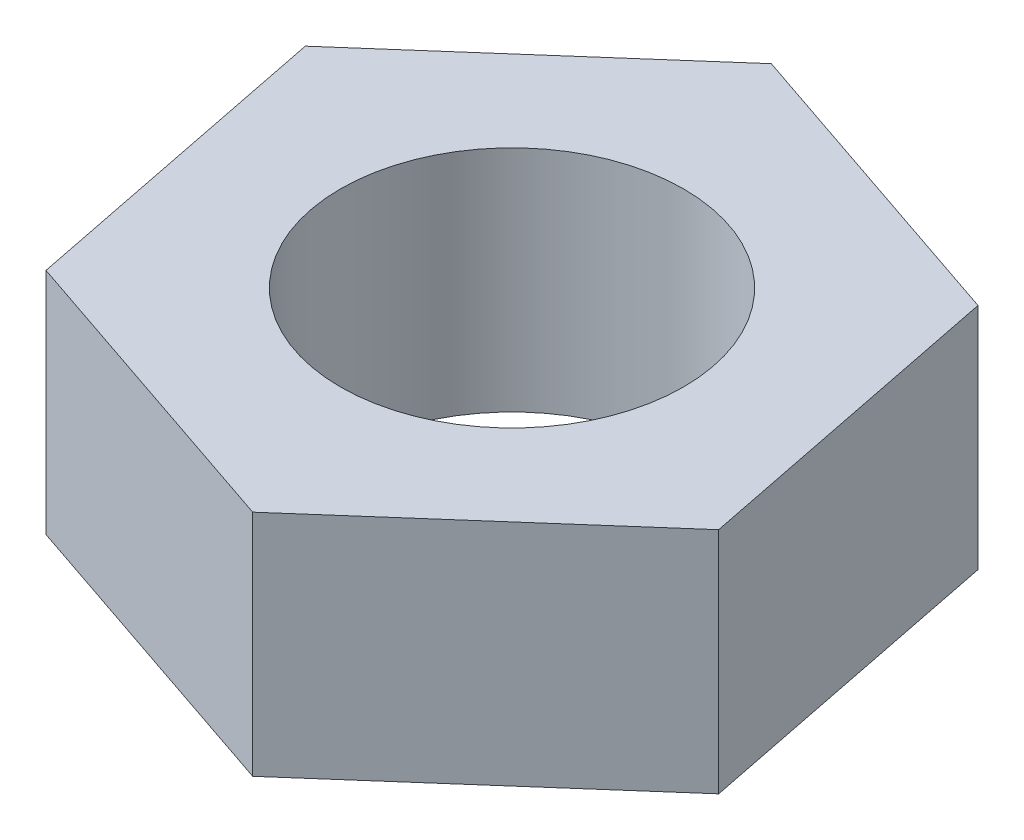
SolidWorks part; units mm, degrees
ref_plane "Front Plane" through (0, 0, 0) normal (0, 0, 1) x (1, 0, 0)
ref_plane "Top Plane" through (0, 0, 0) normal (0, 1, 0) x (1, 0, 0)
ref_plane "Right Plane" through (0, 0, 0) normal (1, 0, 0) x (0, 0, -1)
sketch "Sketch1" plane through (0, 0, 0) normal (0, 1, 0) x (1, 0, 0)
  line L13 (0, 12.5) -> (0.1674, 12.5)
  line L15 (10.8484, 9.5208) -> (-2.8211, 14.1554)
  line L16 (-2.8211, 14.1554) -> (-13.6695, 4.6345)
  line L17 (-13.6695, 4.6345) -> (-10.8484, -9.5208)
  line L18 (-10.8484, -9.5208) -> (2.8211, -14.1554)
  line L19 (2.8211, -14.1554) -> (13.6695, -4.6345)
  line L20 (13.6695, -4.6345) -> (10.8484, 9.5208)
  circle A1 centre (0, 0) radius 7.5
  dimension "D1" = 12.5
  dimension "D2" = 15
extrude "Boss-Extrude1" add sketch "Sketch1" along normal blind 10
